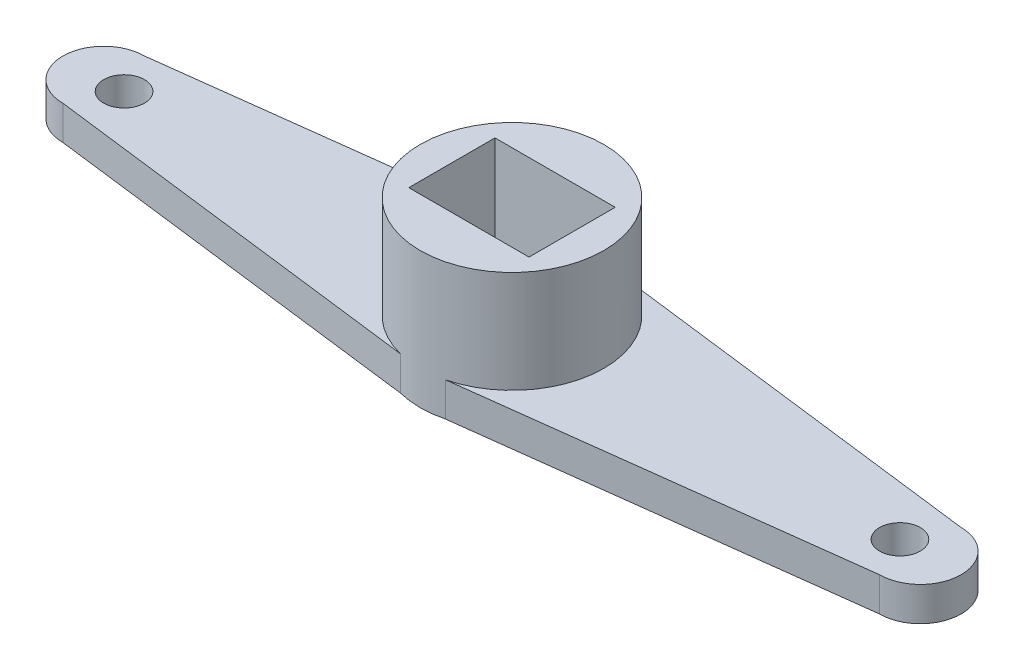
SolidWorks part; units mm, degrees
ref_plane "Front Plane" through (0, 0, 0) normal (0, 0, 1) x (1, 0, 0)
ref_plane "Top Plane" through (0, 0, 0) normal (0, 1, 0) x (1, 0, 0)
ref_plane "Right Plane" through (0, 0, 0) normal (1, 0, 0) x (0, 0, -1)
sketch "Sketch1" plane through (0, 0, 0) normal (0, 1, 0) x (1, 0, 0)
  line L1 (-2.65, -1.9) -> (2.65, -1.9)
  line L2 (-2.65, -1.9) -> (-2.65, 1.9)
  line L3 (-2.65, 1.9) -> (2.65, 1.9)
  line L4 (2.65, -1.9) -> (2.65, 1.9)
  line L5 (-2.65, -1.9) -> (2.65, 1.9) construction
  line L6 (-2.65, 1.9) -> (2.65, -1.9) construction
  circle A0 centre (0, 0) radius 4.05
  dimension "D1" = 5.3
  dimension "D3" = 8.1
  dimension "D2" = 3.8
sketch "Sketch2" plane through (0, 0, 0) normal (0, 1, 0) x (1, 0, 0)
  line L0 (0, 0) -> (18, 0) construction
  line L3 (0, 0) -> (-18, 0) construction
  line L6 (0, 0) -> (0, 4.05) construction
  line L7 (0, 0) -> (0, -4.05) construction
  line L8 (-18, 1.8) -> (0, 4.05)
  line L9 (0, 4.05) -> (18, 1.8)
  line L10 (18, -1.8) -> (0, -4.05)
  line L11 (0, -4.05) -> (-18, -1.8)
  arc A3 (-18, 1.8) -> (-18, -1.8) centre (-18, 0) ccw
  arc A4 (18, 1.8) -> (18, -1.8) centre (18, 0) cw
  dimension "D2" = 18
  dimension "D1" = 18
extrude "Boss-Extrude1" add sketch "Sketch1" along normal blind 6
extrude "Boss-Extrude2" add sketch "Sketch2" along normal blind 1.5
sketch "Sketch3" plane through (0, 0, 0) normal (0, 1, 0) x (1, 0, 0)
  line L0 (-23.85, 0) -> (-2.65, 0) construction
  line L1 (-2.65, -1.9) -> (2.65, -1.9)
  line L2 (-2.65, -1.9) -> (-2.65, 1.9)
  line L3 (-2.65, 1.9) -> (2.65, 1.9)
  line L4 (2.65, -1.9) -> (2.65, 1.9)
  line L5 (-2.65, -1.9) -> (2.65, 1.9) construction
  line L6 (-2.65, 1.9) -> (2.65, -1.9) construction
  line L7 (2.65, 0) -> (23.85, 0) construction
  arc A2 (-22.05, 1.8) -> (-22.05, -1.8) centre (-22.05, 0) ccw construction
  arc A3 (22.05, -1.8) -> (22.05, 1.8) centre (22.05, 0) ccw construction
  circle A4 centre (-17.1, 0) radius 0.9
  circle A5 centre (17.1, 0) radius 0.9
  point P0 (0, 0)
  point P21 (0, 0)
extrude "Cut-Extrude1" cut sketch "Sketch3" along normal blind 1.5
